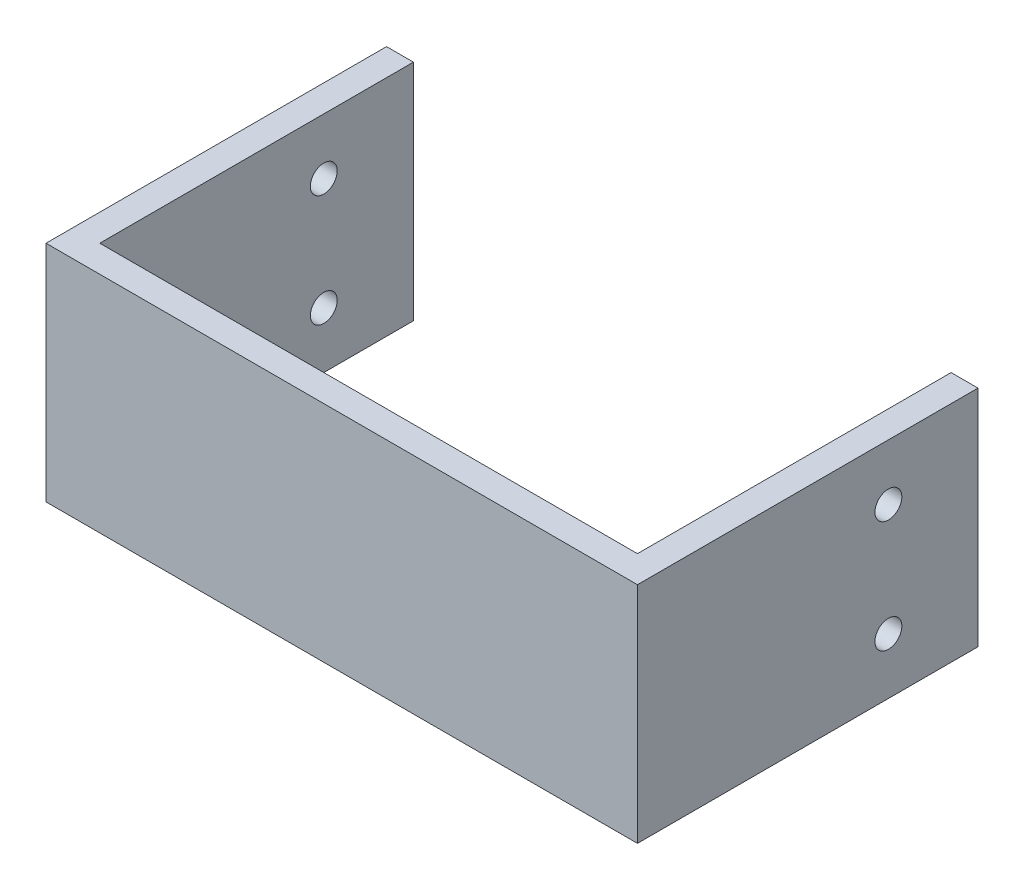
SolidWorks part; units mm, degrees
ref_plane "前视基准面" through (0, 0, 0) normal (0, 0, 1) x (1, 0, 0)
ref_plane "上视基准面" through (0, 0, 0) normal (0, 1, 0) x (1, 0, 0)
ref_plane "右视基准面" through (0, 0, 0) normal (1, 0, 0) x (0, 0, -1)
sketch "草图1" plane through (0, 0, 0) normal (0, 0, 1) x (1, 0, 0)
  line L1 (0, 0) -> (66, 0)
  line L2 (0, 0) -> (0, -25)
  line L3 (0, -25) -> (66, -25)
  line L4 (66, 0) -> (66, -25)
  dimension "D1" = 66
  dimension "D2" = 25
extrude "凸台-拉伸1" add sketch "草图1" along normal blind 3
sketch "草图2" plane through (0, 0, 0) normal (0, 0, -1) x (-1, 0, 0)
  line L0 (-33, 0) -> (-33, -25) construction
  line L1 (-66, 0) -> (0, 0) construction
  line L2 (0, -25) -> (-66, -25) construction
  line L3 (-3, 0) -> (-3, -25)
  line L4 (-66, 0) -> (-63, 0)
  line L5 (-66, 0) -> (-66, -25)
  line L6 (-66, -25) -> (-63, -25)
  line L7 (-63, 0) -> (-63, -25)
  line L8 (0, -25) -> (-3, -25)
  line L9 (0, 0) -> (0, -25)
  line L10 (0, 0) -> (-3, 0)
  dimension "D1" = 3
extrude "凸台-拉伸2" add sketch "草图2" along normal blind 35
sketch "草图3" plane through (0, 0, 0) normal (-1, 0, 0) x (0, 0, 1)
  line L0 (-25, 0) -> (-25, -25) construction
  line L1 (3, 0) -> (-35, 0) construction
  line L2 (3, -25) -> (-35, -25) construction
  line L3 (-35, -12.5) -> (-12.0509, -12.5) construction
  line L4 (-35, -25) -> (-35, 0) construction
  line L5 (-30.1129, -12.5) -> (-30.1129, 0) construction
  line L6 (-30.1129, -6.25) -> (-7.0592, -6.25) construction
  circle A0 centre (-25, -6.25) radius 1.5
  circle A1 centre (-25, -18.75) radius 1.5
  dimension "D2" = 3
  dimension "D1" = 10
extrude "切除-拉伸1" cut sketch "草图3" against normal through all
